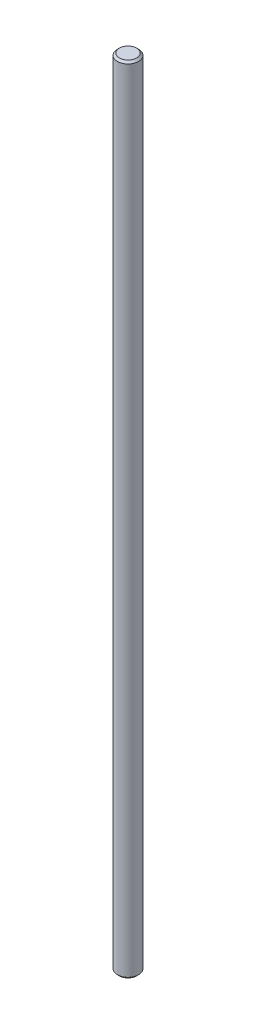
SolidWorks part; units mm, degrees
ref_plane "Front Plane" through (0, 0, 0) normal (0, 0, 1) x (1, 0, 0)
ref_plane "Top Plane" through (0, 0, 0) normal (0, 1, 0) x (1, 0, 0)
ref_plane "Right Plane" through (0, 0, 0) normal (1, 0, 0) x (0, 0, -1)
sketch "Sketch1" plane through (0, 0, 0) normal (0, 1, 0) x (1, 0, 0)
  circle A0 centre (0, 0) radius 4
  dimension "D1" = 8
extrude "Boss-Extrude1" add sketch "Sketch1" along normal blind 300 contours A0
chamfer "Chamfer1" distance 0.75 angle 45 2 edges at (0, 0, 4) (0, 300, 4)
